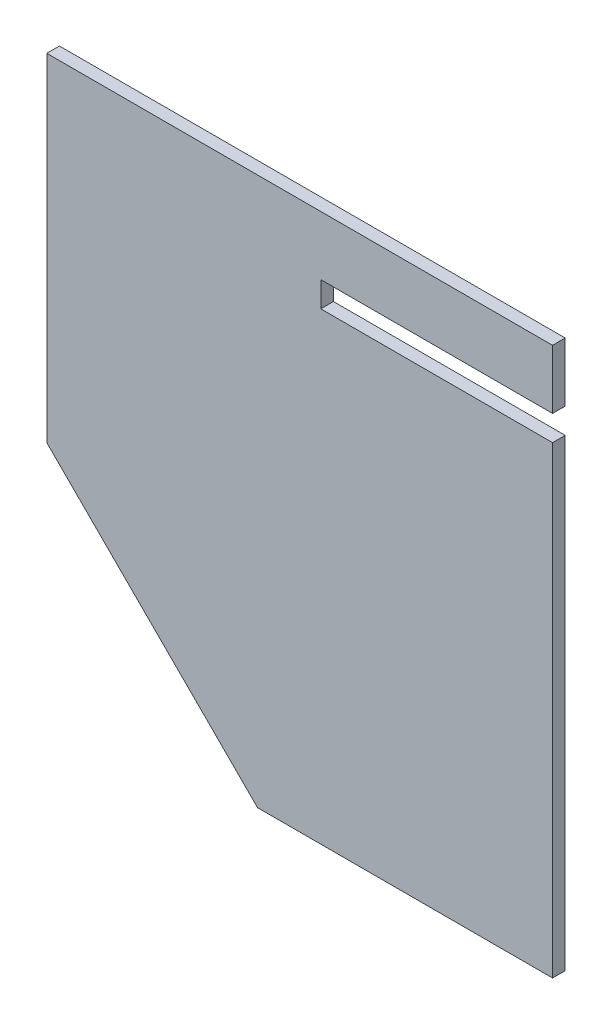
SolidWorks part; units mm, degrees
ref_plane "Ebene vorne" through (0, 0, 0) normal (0, 0, 1) x (1, 0, 0)
ref_plane "Ebene oben" through (0, 0, 0) normal (0, 1, 0) x (1, 0, 0)
ref_plane "Ebene rechts" through (0, 0, 0) normal (1, 0, 0) x (0, 0, -1)
sketch "Skizze1" plane through (0, 0, 0) normal (0, 0, 1) x (1, 0, 0)
  line L0 (0, 0) -> (70, 0)
  line L1 (70, 0) -> (70, 110)
  line L2 (70, 110) -> (15, 110)
  line L3 (15, 110) -> (15, 116)
  line L4 (15, 116) -> (70, 116)
  line L5 (70, 116) -> (70, 130)
  line L6 (70, 130) -> (-50, 130)
  line L7 (-50, 130) -> (-50, 50)
  line L8 (-50, 50) -> (0, 0)
  dimension "D1" = 70
  dimension "D2" = 6
  dimension "D3" = 14
  dimension "D4" = 130
  dimension "D5" = 55
  dimension "D7" = 120
  dimension "D8" = 80
extrude "Aufsatz-Linear austragen1" add sketch "Skizze1" along normal blind 3
